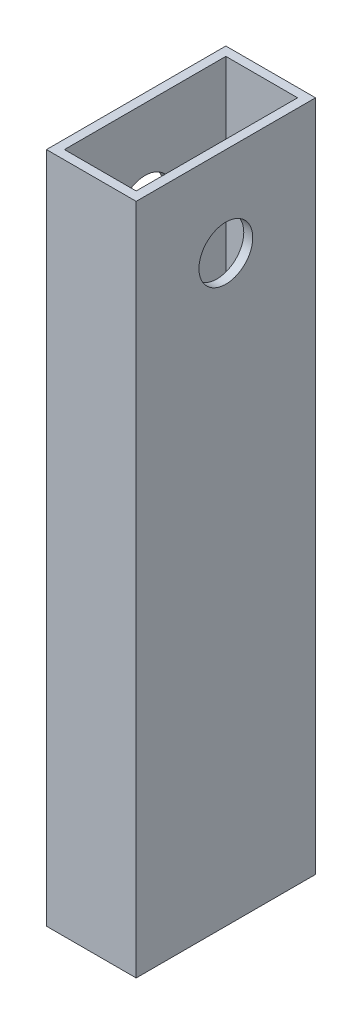
SolidWorks part; units mm, degrees
ref_plane "Front Plane" through (0, 0, 0) normal (0, 0, 1) x (1, 0, 0)
ref_plane "Top Plane" through (0, 0, 0) normal (0, 1, 0) x (1, 0, 0)
ref_plane "Right Plane" through (0, 0, 0) normal (1, 0, 0) x (0, 0, -1)
sketch "Sketch1" plane through (0, 0, 0) normal (0, 1, 0) x (1, 0, 0)
  line L0 (-4, 9) -> (4, 9)
  line L1 (-5, -10) -> (5, -10)
  line L2 (-5, -10) -> (-5, 10)
  line L3 (-5, 10) -> (5, 10)
  line L4 (5, -10) -> (5, 10)
  line L5 (-5, -10) -> (5, 10) construction
  line L6 (-5, 10) -> (5, -10) construction
  line L7 (4, -9) -> (4, 9)
  line L8 (-4, -9) -> (4, -9)
  line L9 (-4, -9) -> (-4, 9)
  point P0 (0, 0)
  dimension "D2" = 10
  dimension "D3" = 20
  dimension "D1" = 1
extrude "Boss-Extrude1" add sketch "Sketch1" along normal blind 75
sketch "Sketch2" plane through (5, 0, 0) normal (1, 0, 0) x (0, 0, -1)
  line L0 (0, 0) -> (0, 65) construction
  line L1 (-10, 0) -> (10, 0) construction
  line L2 (-10, 75) -> (10, 75) construction
  circle A0 centre (0, 65) radius 3
  dimension "D1" = 6
  dimension "D2" = 10
  dimension "D3" = 65
extrude "Cut-Extrude1" cut sketch "Sketch2" against normal through all
